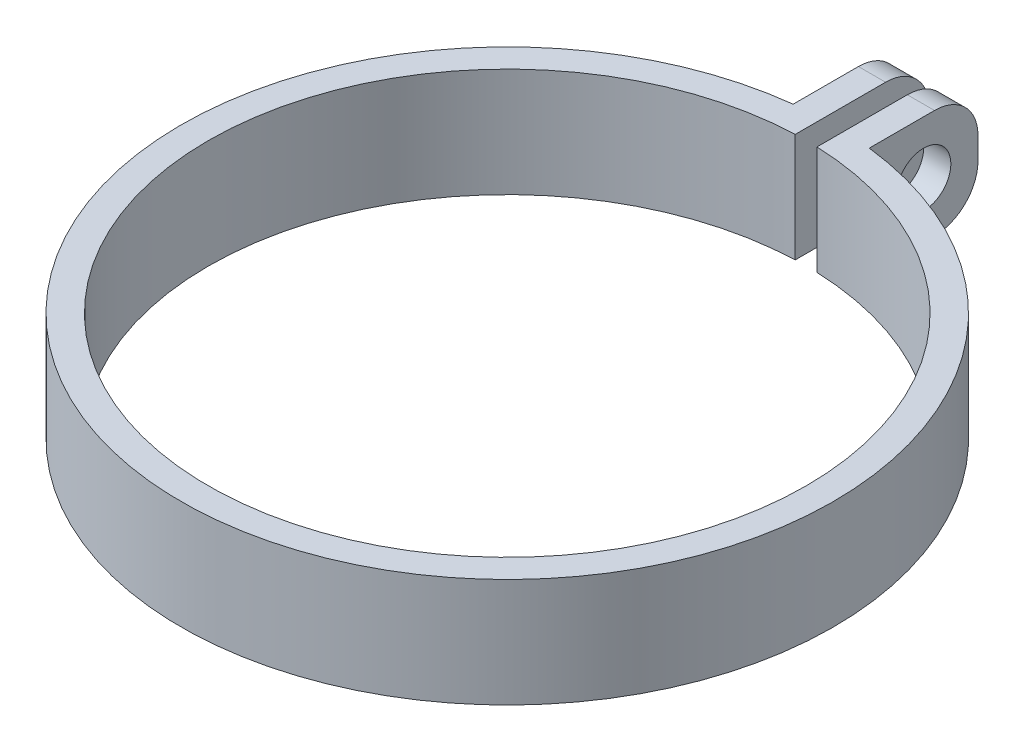
SolidWorks part; units mm, degrees
ref_plane "Alzado" through (0, 0, 0) normal (0, 0, 1) x (1, 0, 0)
ref_plane "Planta" through (0, 0, 0) normal (0, 1, 0) x (1, 0, 0)
ref_plane "Vista lateral" through (0, 0, 0) normal (1, 0, 0) x (0, 0, -1)
sketch "Croquis2" plane through (0, 0, 0) normal (0, 1, 0) x (1, 0, 0)
  line L0 (0, 0) -> (0, 27.5) construction
  line L1 (-1, 39.7951) -> (-1, 27.4818)
  line L2 (-1, 39.7951) -> (-3.5, 39.7951)
  line L3 (-3.5, 39.7951) -> (-3.5, 29.7951)
  line L4 (1, 27.4818) -> (1, 39.7951)
  line L5 (1, 39.7951) -> (3.5, 39.7951)
  line L6 (3.5, 39.7951) -> (3.5, 29.7951)
  line L7 (0, 30) -> (0, 46.2775) construction
  arc A0 (-1, 27.4818) -> (1, 27.4818) centre (0, 0) ccw
  arc A1 (-3.5, 29.7951) -> (3.5, 29.7951) centre (0, 0) ccw
  dimension "D1" = 55
  dimension "D2" = 60
  dimension "D3" = 10
  dimension "D4" = 10
  dimension "D5" = 2.5
  dimension "D6" = 1
  dimension "D7" = 1
  dimension "D8" = 2.5
extrude "Saliente-Extruir1" add sketch "Croquis2" along normal blind 10
sketch "Croquis3" plane through (-3.5, 0, 0) normal (-1, 0, 0) x (0, 0, 1)
  line L0 (-39.7951, 0) -> (-29.7951, 10) construction
  circle A0 centre (-34.7951, 5) radius 2.5
  dimension "D1" = 5
extrude "Cortar-Extruir1" cut sketch "Croquis3" against normal blind 10
fillet "Redondeo1" radius 4 4 edges at (-2.25, 10, -39.7951) (2.25, 10, -39.7951) (2.25, 0, -39.7951) (-2.25, 0, -39.7951)
